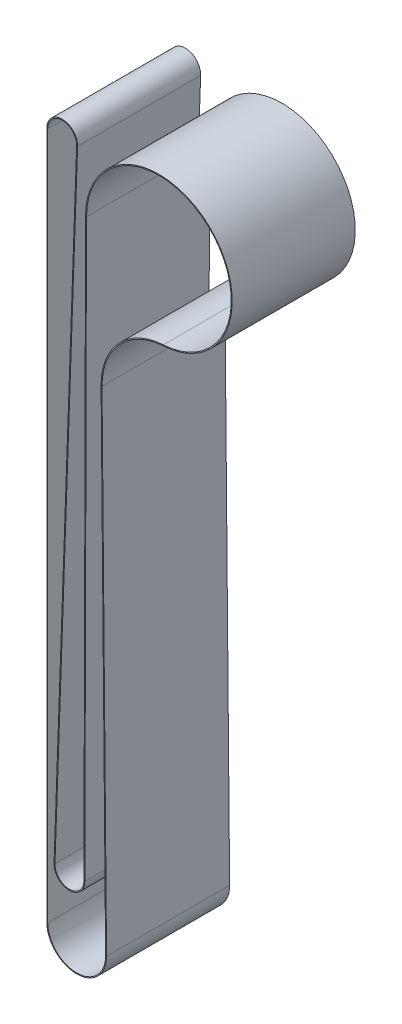
SolidWorks part; units mm, degrees
material "Corrugated Paper"
ref_plane "Front Plane" through (0, 0, 0) normal (0, 0, 1) x (1, 0, 0)
ref_plane "Top Plane" through (0, 0, 0) normal (0, 1, 0) x (1, 0, 0)
ref_plane "Right Plane" through (0, 0, 0) normal (1, 0, 0) x (0, 0, -1)
sketch "Sketch1" plane through (0, 0, 0) normal (0, 0, 1) x (1, 0, 0)
  line L0 (4, 43) -> (4, 173)
  line L1 (4, 173) -> (4, 205)
  line L2 (11.9974, 204.857) -> (5.7487, 30.1521)
  line L3 (14.254, 29.9877) -> (14.7131, 189.2432)
  line L4 (18.7468, 150.8315) -> (19.9997, 15.0738)
  line L5 (4, 15) -> (4, 43)
  line L6 (3.746, 15) -> (3.746, 43)
  line L7 (3.746, 43) -> (3.746, 173)
  line L8 (3.746, 173) -> (3.746, 205)
  line L9 (12.2513, 204.8479) -> (6.0026, 30.143)
  line L10 (14, 29.9885) -> (14.4591, 189.244)
  line L11 (19.0008, 150.8339) -> (20.2536, 15.0762)
  line L12 (0, 173) -> (0, 216) construction
  line L13 (0, 216) -> (60, 216) construction
  line L14 (60, 216) -> (60, 0) construction
  line L15 (60, 0) -> (0, 0) construction
  line L16 (0, 0) -> (0, 43) construction
  line L17 (3, 173) -> (3, 213) construction
  line L18 (3, 213) -> (57, 213) construction
  line L19 (57, 213) -> (57, 3) construction
  line L20 (57, 3) -> (3, 3) construction
  line L21 (3, 3) -> (3, 43) construction
  line L22 (0, 173) -> (3, 173) construction
  line L23 (0, 43) -> (3, 43) construction
  arc A0 (4, 205) -> (11.9974, 204.857) centre (8, 205) cw
  arc A1 (5.7487, 30.1521) -> (14.254, 29.9877) centre (10, 30) ccw
  arc A2 (14.7131, 189.2432) -> (35.9087, 169.2213) centre (34.713, 189.1856) cw
  arc A3 (35.9087, 169.2213) -> (18.7468, 150.8315) centre (37, 151) ccw
  arc A4 (19.9997, 15.0738) -> (4, 15) centre (12, 15) cw
  circle A5 centre (8, 205) radius 2.5 construction
  circle A6 centre (34.713, 189.1856) radius 2.5 construction
  circle A7 centre (10, 30) radius 2.5 construction
  circle A8 centre (12, 15) radius 2.5 construction
  arc A9 (3.746, 205) -> (12.2513, 204.8479) centre (8, 205) cw
  arc A10 (6.0026, 30.143) -> (14, 29.9885) centre (10, 30) ccw
  arc A11 (14.4591, 189.244) -> (35.9239, 168.9678) centre (34.713, 189.1856) cw
  arc A12 (35.9239, 168.9678) -> (19.0008, 150.8339) centre (37, 151) ccw
  arc A13 (20.2536, 15.0762) -> (3.746, 15) centre (12, 15) cw
  arc A14 (35.9087, 169.2213) -> (18.7468, 150.8315) centre (37, 151) ccw construction
  circle A15 centre (37, 151) radius 18 construction
  circle A16 centre (12, 15) radius 8 construction
  circle A17 centre (37, 109) radius 14 construction
  circle A18 centre (37, 151) radius 2.5 construction
  circle A19 centre (37, 151) radius 16 construction
  circle A20 centre (37, 109) radius 5 construction
  circle A21 centre (37, 130) radius 16 construction
  circle A22 centre (37, 130) radius 5 construction
  circle A23 centre (37, 130) radius 2.5 construction
  point P42 (4, 108)
  point P45 (60, 108)
  point P53 (0, 0)
  point P61 (0, 0)
  dimension "D2" = 4
  dimension "D3" = 4
  dimension "D4" = 20
  dimension "D5" = 18
  dimension "D7" = 8
  dimension "D8" = 832
  dimension "D9" = 5
  dimension "D22" = 28
  dimension "D23" = 37
  dimension "D24" = 10
  dimension "D25" = 32
  dimension "D26" = 32
  dimension "D27" = 10
  dimension "D1" = 130
  dimension "D6" = 28
  dimension "D11" = 13
  dimension "D12" = 43
  dimension "D13" = 32
  dimension "D14" = 60
  dimension "D15" = 12
  dimension "D16" = 10
  dimension "D17" = 216
  dimension "D19" = 22
  dimension "D10" = 0.254
  dimension "D20" = 3
extrude "Boss-Extrude1" add sketch "Sketch1" along normal blind 34
sketch "Sketch3" plane through (3.746, 0, 0) normal (-1, 0, 0) x (0, 0, 1)
  line L0 (0, 108) -> (34, 108) construction
  line L1 (0, 205) -> (0, 15) construction
  line L2 (34, 205) -> (34, 15) construction
  line L4 (0, 121) -> (34, 121)
  line L6 (0, 43) -> (34, 43)
  line L12 (0, 69) -> (34, 69)
  line L13 (0, 147) -> (34, 147)
  line L14 (0, 173) -> (34, 173)
  line L15 (0, 121) -> (0, 147) construction
  line L16 (0, 95) -> (34, 95)
  line L17 (0, 95) -> (34, 95) [skipped]
  line L18 (0, 95) -> (34, 95) [skipped]
  line L19 (0, 69) -> (34, 69) [skipped]
  line L20 (0, 121) -> (34, 121) [skipped]
  line L21 (0, 121) -> (34, 121) [skipped]
  line L22 (0, 147) -> (34, 147) [skipped]
  point P6 (0, 147)
  point P16 (34, 121)
  point P20 (34, 121)
  dimension "D1" = 108
  dimension "D2" = 13
  dimension "D5" = 26
  dimension "D6" = 26
  dimension "D3" = 4
  dimension "D4" = 3
split line "Split Line6"
